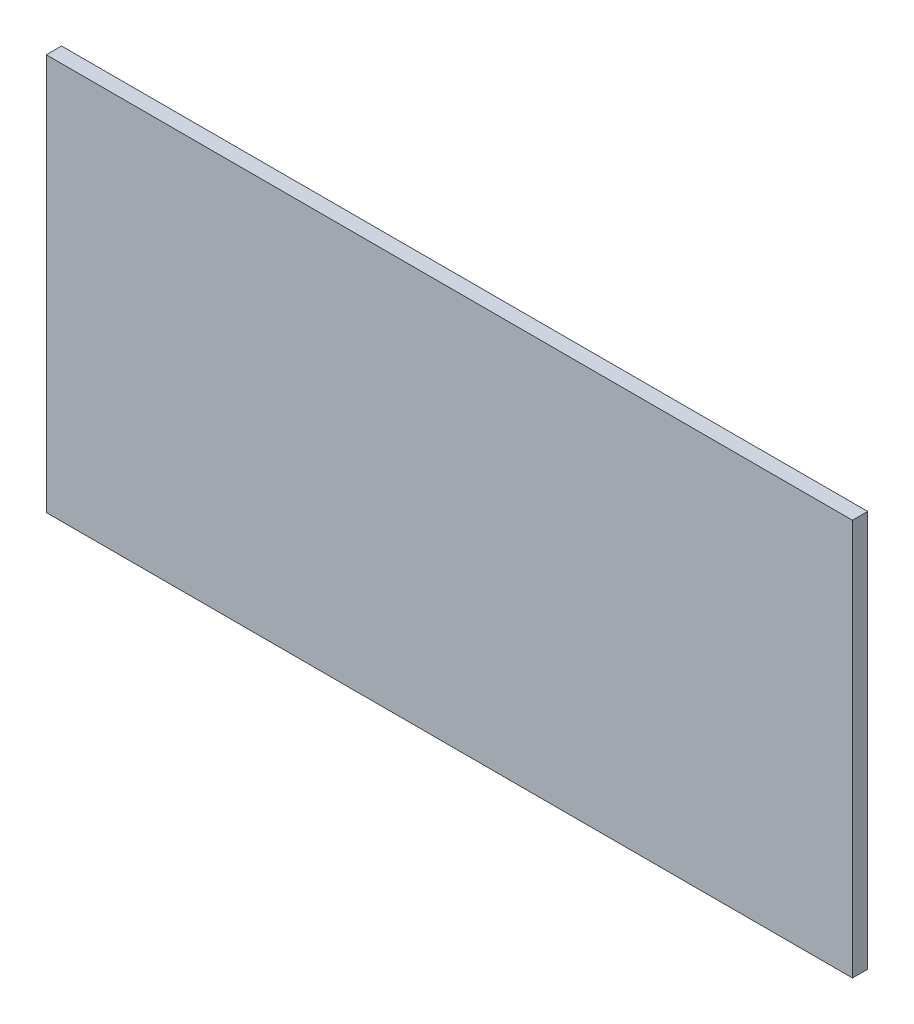
SolidWorks part; units mm, degrees
ref_plane "Front Plane" through (0, 0, 0) normal (0, 0, 1) x (1, 0, 0)
ref_plane "Top Plane" through (0, 0, 0) normal (0, 1, 0) x (1, 0, 0)
ref_plane "Right Plane" through (0, 0, 0) normal (1, 0, 0) x (0, 0, -1)
sketch "Sketch1" plane through (0, 0, 0) normal (0, 0, 1) x (1, 0, 0)
  line L1 (335.7562, 165.1) -> (-335.7563, 165.1)
  line L2 (335.7562, 165.1) -> (335.7562, -165.1)
  line L3 (335.7562, -165.1) -> (-335.7563, -165.1)
  line L4 (-335.7563, 165.1) -> (-335.7563, -165.1)
  line L5 (335.7562, 165.1) -> (-335.7563, -165.1) construction
  line L6 (335.7562, -165.1) -> (-335.7563, 165.1) construction
  point P0 (0, 0)
  dimension "D1" = 330.2
  dimension "D2" = 671.5125
extrude "Boss-Extrude1" add sketch "Sketch1" along normal blind 12.7 contours L4 L3 L2 L1
